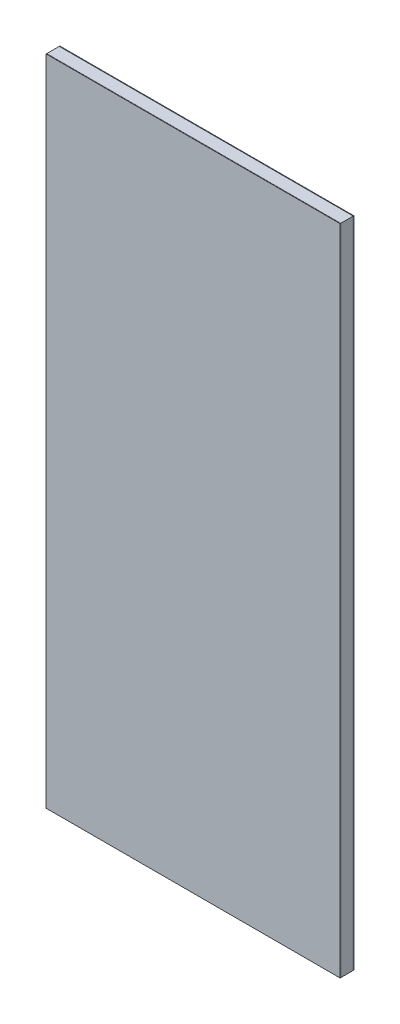
SolidWorks part; units mm, degrees
other "TRAVESSA H SUPERIOR"
other "TRAVESSA H CENTRAL"
other "TRAVESSA H INFERIOR"
other "PERFIL INFERIOR"
other "PERFIL DIREITO"
other "PERFIL SUPERIOR"
other "PERFIL ESQUERDO"
other "PAINEL VERSO"
other "PAINEL FRONTAL"
other "TRAVESSA E SUPERIOR"
other "TRAVESSA C SUPERIOR"
other "TRAVESSA C INFERIOR"
other "TRAVESSA E INFERIOR"
ref_plane "Default Plane" through (-450, 1000, 19) normal (0, -1, 0) x (-1, 0, 0)
sketch3d "Caixa delimitadora_PERFIL VERTICAL"
  line L0 (0, 39, 0) -> (-50, 39, 0) construction
  line L1 (-50, 39, 0) -> (-50, -1, 0) construction
  line L2 (-50, -1, 0) -> (0, -1, 0) construction
  line L3 (0, -1, 0) -> (0, 39, 0) construction
  line L4 (0, 39, 2000) -> (-50, 39, 2000) construction
  line L5 (-50, 39, 2000) -> (-50, -1, 2000) construction
  line L6 (-50, -1, 2000) -> (0, -1, 2000) construction
  line L7 (0, -1, 2000) -> (0, 39, 2000) construction
  line L8 (0, 39, 0) -> (0, 39, 2000) construction
  line L9 (-50, 39, 0) -> (-50, 39, 2000) construction
  line L10 (-50, -1, 0) -> (-50, -1, 2000) construction
  line L11 (0, -1, 0) -> (0, -1, 2000) construction
material "AISI 1020 Aço, laminado a frio"
ref_plane "Default Plane" through (450, 1000, -19) normal (-1, 0, 0) x (0, 0, 1)
sketch3d "Caixa delimitadora_PERFIL HORIZONTAL"
  line L0 (39, 0, 0) -> (39, -50, 0) construction
  line L1 (39, -50, 0) -> (-1, -50, 0) construction
  line L2 (-1, -50, 0) -> (-1, 0, 0) construction
  line L3 (-1, 0, 0) -> (39, 0, 0) construction
  line L4 (39, 0, 900) -> (39, -50, 900) construction
  line L5 (39, -50, 900) -> (-1, -50, 900) construction
  line L6 (-1, -50, 900) -> (-1, 0, 900) construction
  line L7 (-1, 0, 900) -> (39, 0, 900) construction
  line L8 (39, 0, 0) -> (39, 0, 900) construction
  line L9 (39, -50, 0) -> (39, -50, 900) construction
  line L10 (-1, -50, 0) -> (-1, -50, 900) construction
  line L11 (-1, 0, 0) -> (-1, 0, 900) construction
material "AISI 1020 Aço, laminado a frio"
ref_plane "Default Plane" through (400, -475, -19) normal (-1, 0, 0) x (0, 0, 1)
sketch3d "Caixa delimitadora_TRAVESSAS HORIZONTAIS"
  line L0 (-1, 0, 0) -> (-1, -50, 0) construction
  line L1 (-1, -50, 0) -> (39, -50, 0) construction
  line L2 (39, -50, 0) -> (39, 0, 0) construction
  line L3 (39, 0, 0) -> (-1, 0, 0) construction
  line L4 (-1, 0, 800) -> (-1, -50, 800) construction
  line L5 (-1, -50, 800) -> (39, -50, 800) construction
  line L6 (39, -50, 800) -> (39, 0, 800) construction
  line L7 (39, 0, 800) -> (-1, 0, 800) construction
  line L8 (-1, 0, 0) -> (-1, 0, 800) construction
  line L9 (-1, -50, 0) -> (-1, -50, 800) construction
  line L10 (39, -50, 0) -> (39, -50, 800) construction
  line L11 (39, 0, 0) -> (39, 0, 800) construction
material "AISI 1020 Aço, laminado a frio"
ref_plane "Default Plane" through (450, -1000, 21) normal (0, 0, -1) x (-1, 0, 0)
sketch3d "Caixa delimitadora_FECHAMENTOS"
  line L0 (0, 2000, 0) -> (0, 0, 0) construction
  line L1 (0, 0, 0) -> (900, 0, 0) construction
  line L2 (900, 0, 0) -> (900, 2000, 0) construction
  line L3 (900, 2000, 0) -> (0, 2000, 0) construction
  line L4 (0, 2000, 1) -> (0, 0, 1) construction
  line L5 (0, 0, 1) -> (900, 0, 1) construction
  line L6 (900, 0, 1) -> (900, 2000, 1) construction
  line L7 (900, 2000, 1) -> (0, 2000, 1) construction
  line L8 (0, 2000, 0) -> (0, 2000, 1) construction
  line L9 (0, 0, 0) -> (0, 0, 1) construction
  line L10 (900, 0, 0) -> (900, 0, 1) construction
  line L11 (900, 2000, 0) -> (900, 2000, 1) construction
material "6063-T6"
ref_plane "Default Plane" through (325, 525, -19) normal (0, 1, 0) x (1, 0, 0)
sketch3d "Caixa delimitadora_TRAVESSAS VERTICAIS EXT."
  line L0 (0, 1, 0) -> (-50, 1, 0) construction
  line L1 (-50, 1, 0) -> (-50, -39, 0) construction
  line L2 (-50, -39, 0) -> (0, -39, 0) construction
  line L3 (0, -39, 0) -> (0, 1, 0) construction
  line L4 (0, 1, 425) -> (-50, 1, 425) construction
  line L5 (-50, 1, 425) -> (-50, -39, 425) construction
  line L6 (-50, -39, 425) -> (0, -39, 425) construction
  line L7 (0, -39, 425) -> (0, 1, 425) construction
  line L8 (0, 1, 0) -> (0, 1, 425) construction
  line L9 (-50, 1, 0) -> (-50, 1, 425) construction
  line L10 (-50, -39, 0) -> (-50, -39, 425) construction
  line L11 (0, -39, 0) -> (0, -39, 425) construction
material "AISI 1020 Aço, laminado a frio"
ref_plane "Default Plane" through (325, 25, -19) normal (0, 1, 0) x (1, 0, 0)
sketch3d "Caixa delimitadora_TRAVESSAS VERTICAIS CEN."
  line L0 (0, 1, 0) -> (-50, 1, 0) construction
  line L1 (-50, 1, 0) -> (-50, -39, 0) construction
  line L2 (-50, -39, 0) -> (0, -39, 0) construction
  line L3 (0, -39, 0) -> (0, 1, 0) construction
  line L4 (0, 1, 450) -> (-50, 1, 450) construction
  line L5 (-50, 1, 450) -> (-50, -39, 450) construction
  line L6 (-50, -39, 450) -> (0, -39, 450) construction
  line L7 (0, -39, 450) -> (0, 1, 450) construction
  line L8 (0, 1, 0) -> (0, 1, 450) construction
  line L9 (-50, 1, 0) -> (-50, 1, 450) construction
  line L10 (-50, -39, 0) -> (-50, -39, 450) construction
  line L11 (0, -39, 0) -> (0, -39, 450) construction
material "AISI 1020 Aço, laminado a frio"
material "AISI 1020 Aço, laminado a frio"
ref_plane "Plano frontal" through (0, 0, 0) normal (0, 0, 1) x (1, 0, 0)
ref_plane "Plano superior" through (0, 0, 0) normal (0, 1, 0) x (1, 0, 0)
ref_plane "Plano direito" through (0, 0, 0) normal (1, 0, 0) x (0, 0, -1)
other "Caixa delimitadora"
ref_plane "Default Plane" through (450, -1000, -21) normal (-1, 0, 0) x (0, 0, 1)
sketch "Esboço1" plane through (0, 0, 0) normal (0, 0, 1) x (1, 0, 0)
  line L0 (-450, 500) -> (450, 500)
  line L1 (-450, -1000) -> (450, -1000)
  line L2 (-450, -1000) -> (-450, 1000)
  line L3 (-450, 1000) -> (450, 1000)
  line L4 (450, -1000) -> (450, 1000)
  line L5 (0, 1000) -> (0, -1000) construction
  line L6 (-450, 0) -> (450, 0)
  line L7 (-450, -500) -> (450, -500)
  line L8 (300, -1000) -> (300, -500)
  line L9 (300, -500) -> (300, 0)
  line L10 (300, 0) -> (300, 500)
  line L11 (300, 500) -> (300, 1000)
  point P0 (0, 0)
  dimension "D1" = 150
  dimension "LARGURA" = 900
  dimension "D2" = 500
  dimension "ALTURA" = 2000
  dimension "D3" = 1000
  dimension "D4" = 1500
  dimension "D5" = 500
  dimension "D6" = 500
  dimension "D7" = 500
  dimension "D8" = 500
other "Perfis PERFIL_50X40(1)"
ref_plane "Plano1" through (-425, -1000, 0) normal (0, 1, 0) x (-1, 0, 0)
sketch "Esboço11" plane through (-425, -1000, 0) normal (0, 1, 0) x (-1, 0, 0)
  line L0 (-23.4, -17.4) -> (-23.4, 17.4)
  line L1 (-24, -20) -> (24, -20)
  line L2 (-25, -19) -> (-25, 19)
  line L3 (-24, 20) -> (24, 20)
  line L4 (25, -19) -> (25, 19)
  line L5 (-25, -20) -> (25, 20) construction
  line L6 (-25, 20) -> (25, -20) construction
  line L7 (-22.4, 18.4) -> (22.4, 18.4)
  line L8 (23.4, -17.4) -> (23.4, 17.4)
  line L9 (-22.4, -18.4) -> (22.4, -18.4)
  line L10 (23.4, -18.4) -> (23.4, 18.4) construction
  line L11 (-23.4, -18.4) -> (23.4, -18.4) construction
  line L12 (-23.4, 18.4) -> (23.4, 18.4) construction
  line L13 (-23.4, -18.4) -> (-23.4, 18.4) construction
  line L14 (-25, -20) -> (25, -20) construction
  line L15 (25, -20) -> (25, 20) construction
  line L16 (-25, -20) -> (-25, 20) construction
  line L17 (-25, 20) -> (25, 20) construction
  line L18 (0, 20) -> (0, -20) construction
  line L19 (-25, 0) -> (25, 0) construction
  arc A0 (23.4, -17.4) -> (22.4, -18.4) centre (22.4, -17.4) cw
  arc A1 (22.4, 18.4) -> (23.4, 17.4) centre (22.4, 17.4) cw
  arc A2 (-23.4, 17.4) -> (-22.4, 18.4) centre (-22.4, 17.4) cw
  arc A3 (-23.4, -17.4) -> (-22.4, -18.4) centre (-22.4, -17.4) ccw
  arc A4 (24, -20) -> (25, -19) centre (24, -19) ccw
  arc A5 (-25, 19) -> (-24, 20) centre (-24, 19) cw
  arc A6 (-24, -20) -> (-25, -19) centre (-24, -19) cw
  arc A7 (24, 20) -> (25, 19) centre (24, 19) cw
  point P0 (0, 0)
  point P37 (0, 0)
  dimension "D4" = 1
  dimension "D2" = 50
  dimension "D3" = 40
  dimension "D1" = 1.6
other "Perfis PERFIL_50X40(2)"
ref_plane "Plano2" through (-450, -500, 0) normal (1, 0, 0) x (0, 1, 0)
sketch "Esboço12" plane through (-450, -500, 0) normal (1, 0, 0) x (0, 1, 0)
  line L0 (-23.4, -17.4) -> (-23.4, 17.4)
  line L1 (-24, -20) -> (24, -20)
  line L2 (-25, -19) -> (-25, 19)
  line L3 (-24, 20) -> (24, 20)
  line L4 (25, -19) -> (25, 19)
  line L5 (-25, -20) -> (25, 20) construction
  line L6 (-25, 20) -> (25, -20) construction
  line L7 (-22.4, 18.4) -> (22.4, 18.4)
  line L8 (23.4, -17.4) -> (23.4, 17.4)
  line L9 (-22.4, -18.4) -> (22.4, -18.4)
  line L10 (23.4, -18.4) -> (23.4, 18.4) construction
  line L11 (-23.4, -18.4) -> (23.4, -18.4) construction
  line L12 (-23.4, 18.4) -> (23.4, 18.4) construction
  line L13 (-23.4, -18.4) -> (-23.4, 18.4) construction
  line L14 (-25, -20) -> (25, -20) construction
  line L15 (25, -20) -> (25, 20) construction
  line L16 (-25, -20) -> (-25, 20) construction
  line L17 (-25, 20) -> (25, 20) construction
  line L18 (0, 20) -> (0, -20) construction
  line L19 (-25, 0) -> (25, 0) construction
  arc A0 (23.4, -17.4) -> (22.4, -18.4) centre (22.4, -17.4) cw
  arc A1 (22.4, 18.4) -> (23.4, 17.4) centre (22.4, 17.4) cw
  arc A2 (-23.4, 17.4) -> (-22.4, 18.4) centre (-22.4, 17.4) cw
  arc A3 (-23.4, -17.4) -> (-22.4, -18.4) centre (-22.4, -17.4) ccw
  arc A4 (24, -20) -> (25, -19) centre (24, -19) ccw
  arc A5 (-25, 19) -> (-24, 20) centre (-24, 19) cw
  arc A6 (-24, -20) -> (-25, -19) centre (-24, -19) cw
  arc A7 (24, 20) -> (25, 19) centre (24, 19) cw
  point P0 (0, 0)
  point P37 (0, 0)
  dimension "D4" = 1
  dimension "D2" = 50
  dimension "D3" = 40
  dimension "D1" = 1.6
other "Aparar/Estender1"
sketch "Esboço13" plane through (0, 0, 20) normal (0, 0, 1) x (1, 0, 0)
  line L4 (-450, -1000) -> (450, -1000)
  line L5 (-450, 1000) -> (-450, -1000)
  line L6 (450, 1000) -> (-450, 1000)
  line L7 (450, -1000) -> (450, 1000)
  line L8 (-450, -1000) -> (450, -1000)
  line L9 (-450, 1000) -> (-450, -1000)
  line L10 (450, 1000) -> (-450, 1000)
  line L11 (450, -1000) -> (450, 1000)
  dimension "D1" = 0
extrude "Ressalto-extrusão1" add sketch "Esboço13" along normal blind 1 separate body
mirror "Espelhar1" about plane through (0, 0, 0) normal (0, 0, 1) of bodies 112
sketch "Esboço16" plane through (0, 0, 0) normal (0, 0, 1) x (1, 0, 0)
  line L0 (300, 950) -> (300, 525)
  line L1 (300, 500) -> (300, 1000) construction
  line L2 (400, 950) -> (-400, 950) construction
  line L3 (400, 525) -> (-400, 525) construction
  line L4 (300, 475) -> (300, 25)
  line L5 (400, 475) -> (-400, 475) construction
  line L6 (400, 25) -> (-400, 25) construction
  line L7 (300, -25) -> (300, -475)
  line L8 (400, -25) -> (-400, -25) construction
  line L9 (400, -475) -> (-400, -475) construction
  line L10 (300, -525) -> (300, -950)
  line L11 (400, -525) -> (-400, -525) construction
  line L12 (-400, -950) -> (400, -950) construction
other "Perfis PERFIL_50X40(6)"
ref_plane "Plano4" through (300, 950, 0) normal (0, -1, 0) x (1, 0, 0)
sketch "Esboço17" plane through (300, 950, 0) normal (0, -1, 0) x (1, 0, 0)
  line L0 (-23.4, -17.4) -> (-23.4, 17.4)
  line L1 (-24, -20) -> (24, -20)
  line L2 (-25, -19) -> (-25, 19)
  line L3 (-24, 20) -> (24, 20)
  line L4 (25, -19) -> (25, 19)
  line L5 (-25, -20) -> (25, 20) construction
  line L6 (-25, 20) -> (25, -20) construction
  line L7 (-22.4, 18.4) -> (22.4, 18.4)
  line L8 (23.4, -17.4) -> (23.4, 17.4)
  line L9 (-22.4, -18.4) -> (22.4, -18.4)
  line L10 (23.4, -18.4) -> (23.4, 18.4) construction
  line L11 (-23.4, -18.4) -> (23.4, -18.4) construction
  line L12 (-23.4, 18.4) -> (23.4, 18.4) construction
  line L13 (-23.4, -18.4) -> (-23.4, 18.4) construction
  line L14 (-25, -20) -> (25, -20) construction
  line L15 (25, -20) -> (25, 20) construction
  line L16 (-25, -20) -> (-25, 20) construction
  line L17 (-25, 20) -> (25, 20) construction
  line L18 (0, 20) -> (0, -20) construction
  line L19 (-25, 0) -> (25, 0) construction
  arc A0 (23.4, -17.4) -> (22.4, -18.4) centre (22.4, -17.4) cw
  arc A1 (22.4, 18.4) -> (23.4, 17.4) centre (22.4, 17.4) cw
  arc A2 (-23.4, 17.4) -> (-22.4, 18.4) centre (-22.4, 17.4) cw
  arc A3 (-23.4, -17.4) -> (-22.4, -18.4) centre (-22.4, -17.4) ccw
  arc A4 (24, -20) -> (25, -19) centre (24, -19) ccw
  arc A5 (-25, 19) -> (-24, 20) centre (-24, 19) cw
  arc A6 (-24, -20) -> (-25, -19) centre (-24, -19) cw
  arc A7 (24, 20) -> (25, 19) centre (24, 19) cw
  point P0 (0, 0)
  point P37 (0, 0)
  dimension "D4" = 1
  dimension "D2" = 50
  dimension "D3" = 40
  dimension "D1" = 1.6
